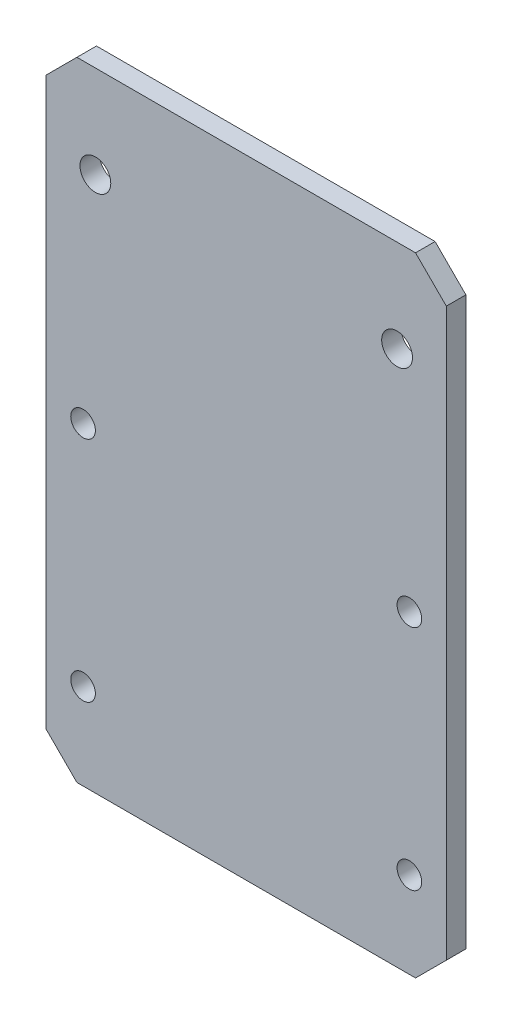
SolidWorks part; units mm, degrees
material "6061-T6 (SS)"
ref_plane "Front Plane" through (0, 0, 0) normal (0, 0, 1) x (1, 0, 0)
ref_plane "Top Plane" through (0, 0, 0) normal (0, 1, 0) x (1, 0, 0)
ref_plane "Right Plane" through (0, 0, 0) normal (1, 0, 0) x (0, 0, -1)
sketch "Sketch1" plane through (0, 0, 0) normal (0, 0, 1) x (1, 0, 0)
  line L0 (-32.5, 36) -> (32.5, 36) construction
  line L1 (-32.5, -51) -> (32.5, -51)
  line L2 (-32.5, -51) -> (-32.5, 51)
  line L3 (-32.5, 51) -> (32.5, 51)
  line L4 (32.5, -51) -> (32.5, 51)
  line L5 (0, 51) -> (0, -51) construction
  line L6 (-32.5, 0) -> (32.5, 0) construction
  line L7 (-32.5, 16) -> (32.5, 16) construction
  line L8 (-32.5, 14) -> (32.5, 14) construction
  line L9 (-32.5, 14) -> (-32.5, -51) construction
  line L10 (-32.5, -51) -> (32.5, -51) construction
  line L11 (32.5, 14) -> (32.5, -51) construction
  line L12 (0, -51) -> (0, 14) construction
  line L13 (-32.5, -18.5) -> (32.5, -18.5) construction
  circle A0 centre (24.5, 36) radius 2.5
  circle A1 centre (-24.5, 36) radius 2.5
  circle A2 centre (26.5, 0) radius 2
  circle A3 centre (-26.5, 0) radius 2
  circle A4 centre (-26.5, -37) radius 2
  circle A5 centre (26.5, -37) radius 2
  point P0 (0, 0)
  point P6 (0, -18.5)
  dimension "D5" = 5
  dimension "D6" = 8
  dimension "D7" = 4
  dimension "D8" = 53
  dimension "D9" = 37
  dimension "D1" = 65
  dimension "D2" = 20
  dimension "D3" = 2
  dimension "D4" = 15
extrude "Boss-Extrude1" add sketch "Sketch1" along normal blind 3.175
chamfer "Chamfer1" distance 5 angle 45 4 edges at (-32.5, -51, 1.5875) (32.5, -51, 1.5875) (-32.5, 51, 1.5875) (32.5, 51, 1.5875)
